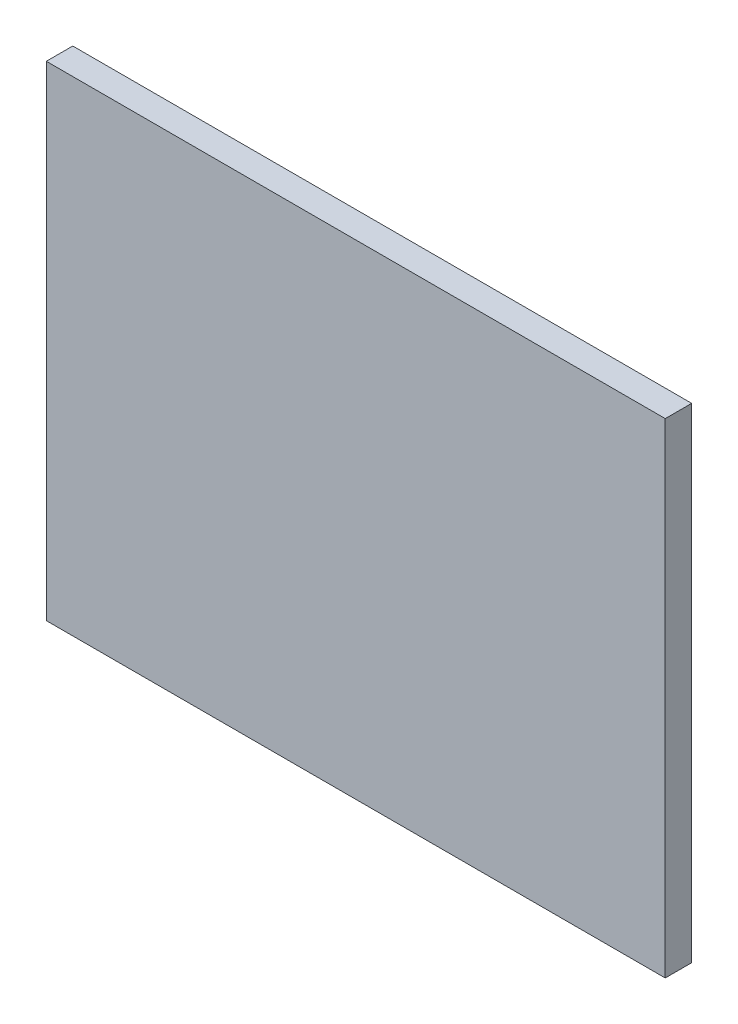
SolidWorks part; units mm, degrees
ref_plane "Front Plane" through (0, 0, 0) normal (0, 0, 1) x (1, 0, 0)
ref_plane "Top Plane" through (0, 0, 0) normal (0, 1, 0) x (1, 0, 0)
ref_plane "Right Plane" through (0, 0, 0) normal (1, 0, 0) x (0, 0, -1)
sketch "Sketch1" plane through (0, 0, 0) normal (0, 0, 1) x (1, 0, 0)
  line L1 (0, 0) -> (107.696, 0)
  line L2 (0, 0) -> (0, 84.3)
  line L3 (0, 84.3) -> (107.696, 84.3)
  line L4 (107.696, 0) -> (107.696, 84.3)
  line L5 (0, 0) -> (107.696, 84.3) construction
  line L6 (0, 84.3) -> (107.696, 0) construction
  point P4 (53.848, 42.15)
  dimension "D1" = 84.3
  dimension "D2" = 107.696
extrude "Boss-Extrude1" add sketch "Sketch1" along normal blind 4.6
equation "\"MDF\"= 4.8mm"
equation "\"Foamcore\"= 4.6mm"
equation "\"GMaterial\"= \"MDF\""
equation "\"PCB\" = 1.6mm"
equation "\"BaseWidth\" = 10in"
equation "\"SkidLength\" = 1in"
equation "\"SkidClearance\" = 0.4in"
equation "\"MotorMountLength\" = 2in"
equation "\"MotorMountWidth\" = \"GMaterial\""
equation "\"MotorMountHeight\" = 2.25in"
equation "\"UnoStackWidth\" = 77.4mm"
equation "\"UnoStackLength\" = 79.8mm"
equation "\"UnoStackHeight\" = 34.2mm"
equation "\"TallHexRiserHeight\" = 22.2mm"
equation "\"PingPongBallSize\" = 40mm"
equation "\"BarrelLength\" = 9in"
equation "\"BarrelSize\" = \"PingPongBallSize\""
equation "\"PlatformLength\" = 4in"
equation "\"PlatformWidth\" = 6in"
equation "\"WheelDiameter\"=2.99213"
equation "\"ServoMountHeight\"=2.49223"
equation "\"ServoGearHeight\" = 0.95330261in"
equation "\"ServoMountLength\"= 1.53774"
equation "\"PivotHoleRadius\"= 0.616358"
equation "\"PlatformMountHeight\" = 3.19"
equation "\"TensionOffSet\"= .3mm"
equation "\"MotorMountWedge\"=0.333333"
equation "\"LaserCutterOffset\"= .3mm"
equation "\"BumperWidth\"=11"
equation "\"PitcherWheelCompression\" = 2.5mm"
equation "\"PitchingWheelWidth\" = 26.2mm"
equation "\"PitchingWheelDiameter\" = 65.5mm"
equation "\"PitchingWheelMountOffset\" = 8.4mm"
equation "\"PitchingWheelInnerDiameter\" = 45.5mm"
equation "\"PitchingWheelBoltShoulder\" = 4.5mm"
equation "\"BrassCouplingLength\" = 18mm"
equation "\"PitchingMotorHeight\" = 57.0mm"
equation "\"PitchingMotorShaftTopHeight\" = \"PitchingMotorHeight\" - 44.1mm"
equation "\"PitchingMotorBodyHeight\" = 38mm"
equation "\"PitchingMotorTopShoulderHeight\" = 40.6mm - \"PitchingMotorBodyHeight\" "
equation "\"PitchingMotorBottomShoulderHeight\" = 40.2mm - \"PitchingMotorBodyHeight\""
equation "\"PitchingMotorBottomShaftHeight\" = \"PitchingMotorHeight\" - \"PitchingMotorShaftTopHeight\" - \"PitchingMotorTopShoulderHeight\" - \"PitchingMotorBodyHeight\" - \"PitchingMotorBottomShoulderHeight\""
equation "\"PitchingMotorShaftDiameter\" = 2.2mm"
equation "\"PitchingMotorBodyDiameter\" = 27.4mm"
equation "\"PitchingMotorTopShoulderDiameter\" = 9.8mm"
equation "\"PitchingMotorBottomShoulderDiameter\" = 9.8mm"
equation "\"BrassCouplingHexSize\" = 12mm"
equation "\"BrassCouplingBoreSize\" = 3.17mm"
equation "\"PitchingMotorMountingHoleDistance\" = 16mm"
equation "\"Acrylic\" = 4.4mm"
equation "\"PitchingMotorDistance\" = \"PitchingWheelDiameter\" + \"PingPongBallSize\" - \"PitcherWheelCompression\"*2"
equation "\"PitchingMotorPlatformOffset\"=1"
equation "\"ServoPlatformOffset\"=1.64173"
equation "\"BallBearingDiameter\" = 22mm"
equation "\"BallBearingWidth\" = 9mm"
equation "\"BallBearingHexShoulder\" = 9mm - 5.9mm"
equation "\"BallBearingHexSize\" = .36in"
equation "\"PlatformMountFootLength\"=0.857143"
equation "\"WheelWidth\"= 26mm"
equation "\"ServoMountReductionBackHeight\"=2.25"
equation "\"PlatformBottomWidthThird\" =  0.857143in"
equation "\"PlatformMountBackReductionHeight\"= 2.5in"
equation "\"PlatformMountBackReductionWidth\"= 3/7in"
equation "\"PlatformMountFrontReductionWidth\" =  1.46226in"
equation "\"PlatformMountFrontReductionHeight\" = 2.5in"
equation "\"HopperLongWallLength\" = 8.646in"
equation "\"HopperShortWallLength\" = 0.9571in"
equation "\"HopperLongCornerLength\"=4.24"
equation "\"D2@Sketch1\"=\"HopperLongCornerLength\""
equation "\"D1@Boss-Extrude1\"=\"Foamcore\""
equation "\"HopperHeight\" = 3.50in - \"Foamcore\""
equation "\"D1@Sketch1\"=\"HopperHeight\""
